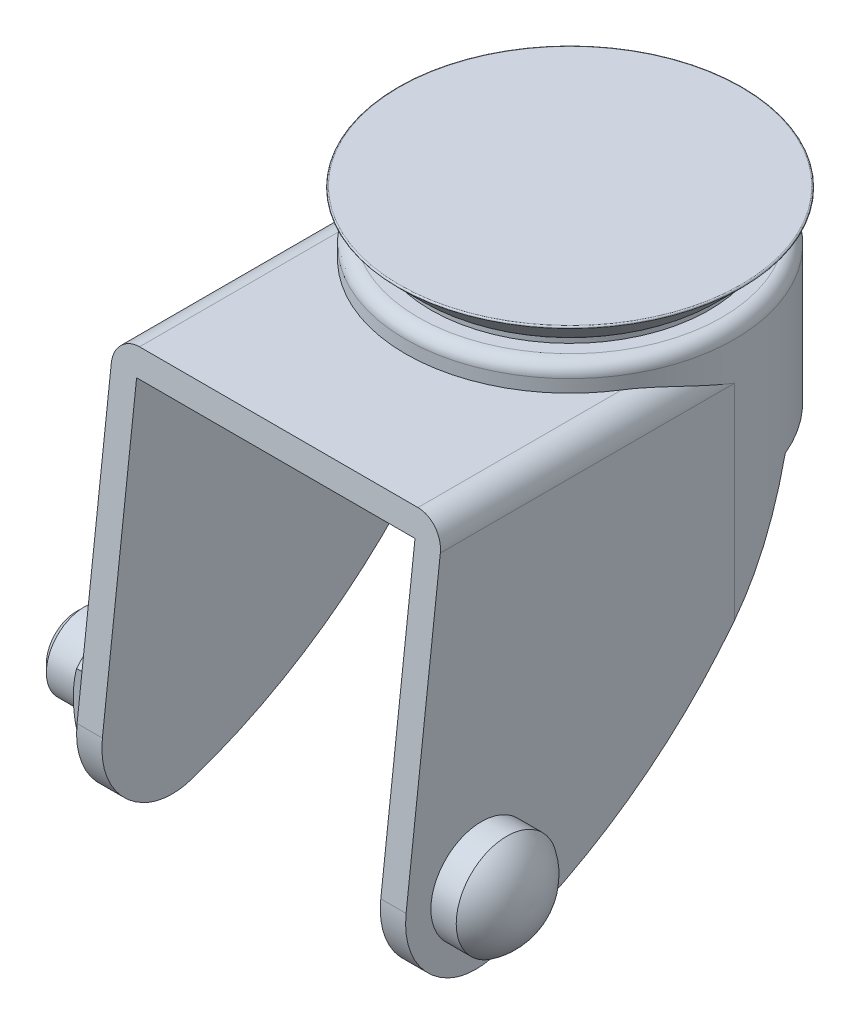
SolidWorks part; units mm, degrees
ref_plane "Front Plane" through (0, 0, 0) normal (0, 0, 1) x (1, 0, 0)
ref_plane "Top Plane" through (0, 0, 0) normal (0, 1, 0) x (1, 0, 0)
ref_plane "Right Plane" through (0, 0, 0) normal (1, 0, 0) x (0, 0, -1)
ref_plane "Plane1" through (0, 0, 0) normal (0, 0, 1) x (1, 0, 0)
sketch "Sketch1" plane through (0, 0, 0) normal (0, 0, 1) x (1, 0, 0)
  line L0 (0, 0) -> (11, 0)
  line L1 (11, 0) -> (11, -3)
  line L2 (11, -3) -> (12, -3)
  line L3 (13, -4) -> (13, -51)
  line L4 (13, -51) -> (0, -51)
  line L5 (0, -51) -> (0, 0)
  line L6 (0, -51) -> (0, 0) construction
  arc A0 (12, -3) -> (13, -4) centre (12, -4) cw
revolve "Revolve1" add sketch "Sketch1" angle 360 about L6
ref_plane "Plane2" through (0, 0, 0) normal (0, 0, 1) x (1, 0, 0)
sketch "Sketch2" plane through (0, 0, 0) normal (0, 0, 1) x (1, 0, 0)
  line L0 (-13, -56) -> (13, -56)
  line L1 (13, -56) -> (13, -7)
  line L2 (11, -5) -> (-11, -5)
  line L3 (-13, -7) -> (-13, -56)
  arc A0 (13, -7) -> (11, -5) centre (11, -7) ccw
  arc A1 (-11, -5) -> (-13, -7) centre (-11, -7) ccw
extrude "Boss-Extrude1" add sketch "Sketch2" along normal blind 60
ref_plane "Plane3" through (0, 0, 0) normal (0, 0, 1) x (1, 0, 0)
sketch "Sketch3" plane through (0, 0, 0) normal (0, 0, 1) x (1, 0, 0)
  line L0 (-11, -7) -> (-11, -58)
  line L1 (-11, -58) -> (11, -58)
  line L2 (11, -58) -> (11, -7)
  line L3 (11, -7) -> (-11, -7)
extrude "Cut-Extrude1" cut sketch "Sketch3" along normal blind 70
ref_plane "Plane4" through (0, -4, 0) normal (0, 1, 0) x (1, 0, 0)
sketch "Sketch4" plane through (0, -4, 0) normal (0, 1, 0) x (1, 0, 0)
  circle A0 centre (0, 0) radius 11
extrude "Cut-Extrude2" cut sketch "Sketch4" against normal blind 51
ref_plane "Plane5" through (0, 0, 0) normal (1, 0, 0) x (0, 0, -1)
sketch "Sketch5" plane through (0, 0, 0) normal (1, 0, 0) x (0, 0, -1)
  line L0 (-150, -4.8) -> (-150, -300)
  line L1 (-150, -300) -> (150, -300)
  line L2 (150, -300) -> (150, -14.8)
  line L3 (150, -14.8) -> (5, -14.8)
  line L4 (-25.96, -30.3084) -> (-23, -4.8)
  line L5 (-23, -4.8) -> (-150, -4.8)
  arc A0 (5, -14.8) -> (-18.8511, -36.6319) centre (-31.629, 1.2723) cw
  arc A1 (-18.8511, -36.6319) -> (-22.69, -36.3632) centre (-20.4483, -31.8939) cw
  arc A2 (-22.69, -36.3632) -> (-25.96, -30.3084) centre (-20, -31) cw
extrude "Cut-Extrude3" cut sketch "Sketch5" against normal blind 200 and the other way blind 200
ref_plane "Plane6" through (0, 0, 20) normal (0, 0, 1) x (1, 0, 0)
sketch "Sketch6" plane through (0, 0, 20) normal (0, 0, 1) x (1, 0, 0)
  line L0 (13, -31) -> (13, -27)
  line L1 (13, -27) -> (15, -27)
  line L2 (17, -31) -> (13, -31)
  line L3 (17, -31) -> (13, -31) construction
  arc A0 (15, -27) -> (17, -31) centre (12.5072, -30.7464) cw
revolve "Revolve2" add sketch "Sketch6" angle 360 about L3
ref_plane "Plane7" through (0, 0, 20) normal (0, 0, 1) x (1, 0, 0)
sketch "Sketch7" plane through (0, 0, 20) normal (0, 0, 1) x (1, 0, 0)
  line L0 (-19, -31) -> (-19, -28.6135)
  line L1 (-19, -28.6135) -> (-18.3865, -28)
  line L2 (-18.3865, -28) -> (-16, -28)
  line L3 (-16, -28) -> (-16, -28.6)
  line L4 (-15, -26.2) -> (-13, -26.2)
  line L5 (-13, -26.2) -> (-13, -31)
  line L6 (-13, -31) -> (-19, -31)
  line L7 (-13, -31) -> (-19, -31) construction
  arc A0 (-16, -28.6) -> (-15, -26.2) centre (-10.0931, -29.6529) cw
revolve "Revolve3" add sketch "Sketch7" angle 360 about L7
ref_plane "Plane8" through (-13, 0, 0) normal (1, 0, 0) x (0, 0, -1)
sketch "Sketch8" plane through (-13, 0, 0) normal (1, 0, 0) x (0, 0, -1)
  line L0 (-23.6, -28.9215) -> (-23.6, -33.0785)
  line L1 (-23.6, -33.0785) -> (-20, -35.1569)
  line L2 (-20, -35.1569) -> (-16.4, -33.0785)
  line L3 (-16.4, -33.0785) -> (-16.4, -28.9215)
  line L4 (-16.4, -28.9215) -> (-20, -26.8431)
  line L5 (-20, -26.8431) -> (-23.6, -28.9215)
  circle A0 centre (-20, -31) radius 5.3
extrude "Cut-Extrude4" cut sketch "Sketch8" against normal blind 200
ref_plane "Plane9" through (0, 0, 0) normal (0, 0, 1) x (1, 0, 0)
sketch "Sketch9" plane through (0, 0, 0) normal (0, 0, 1) x (1, 0, 0)
  line L0 (0, 0) -> (13.5086, 0)
  line L1 (13.5793, -0.1707) -> (11.5429, -2.2071)
  line L2 (10.8358, -2.5) -> (0, -2.5)
  line L3 (0, -2.5) -> (0, 0)
  line L4 (0, -2.5) -> (0, 0) construction
  arc A0 (13.5086, 0) -> (13.5793, -0.1707) centre (13.5086, -0.1) cw
  arc A1 (11.5429, -2.2071) -> (10.8358, -2.5) centre (10.8358, -1.5) cw
revolve "Revolve4" add sketch "Sketch9" angle 360 about L4
